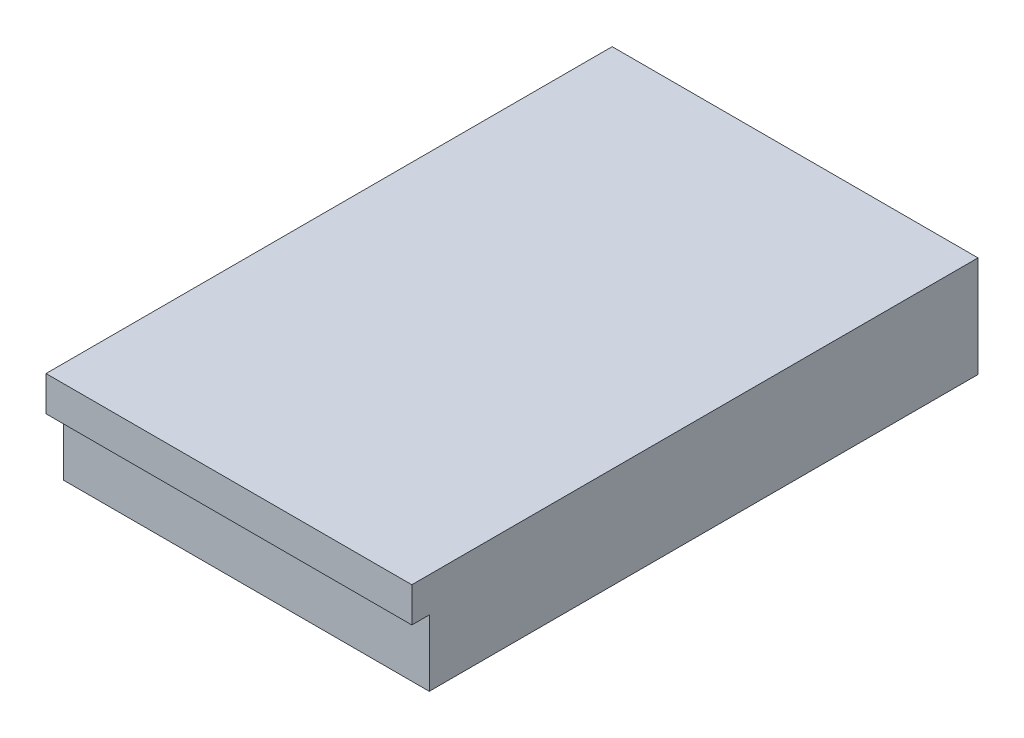
SolidWorks part; units mm, degrees
ref_plane "Front Plane" through (0, 0, 0) normal (0, 0, 1) x (1, 0, 0)
ref_plane "Top Plane" through (0, 0, 0) normal (0, 1, 0) x (1, 0, 0)
ref_plane "Right Plane" through (0, 0, 0) normal (1, 0, 0) x (0, 0, -1)
sketch "Sketch1" plane through (0, 0, 0) normal (0, 1, 0) x (1, 0, 0)
  line L1 (26.67, 40.005) -> (-26.67, 40.005)
  line L2 (26.67, 40.005) -> (26.67, -40.005)
  line L3 (26.67, -40.005) -> (-26.67, -40.005)
  line L4 (-26.67, 40.005) -> (-26.67, -40.005)
  line L5 (26.67, 40.005) -> (-26.67, -40.005) construction
  line L6 (26.67, -40.005) -> (-26.67, 40.005) construction
  point P0 (0, 0)
  dimension "D1" = 80.01
  dimension "D2" = 53.34
extrude "Boss-Extrude1" add sketch "Sketch1" along normal blind 14.732
sketch "Sketch2" plane through (0, 0, 40.005) normal (0, 0, 1) x (1, 0, 0)
  line L0 (26.67, 14.732) -> (26.67, 0) construction
  line L1 (-26.67, 14.732) -> (26.67, 14.732)
  line L2 (-26.67, 14.732) -> (-26.67, 9.652)
  line L3 (-26.67, 9.652) -> (26.67, 9.652)
  line L4 (26.67, 14.732) -> (26.67, 9.652)
  dimension "D1" = 5.08
extrude "Boss-Extrude2" add sketch "Sketch2" along normal blind 2.54
sketch "Sketch3" plane through (0, 14.732, 0) normal (0, 1, 0) x (-1, 0, 0)
  line L0 (26.67, -19.2566) -> (26.67, 42.545) construction
  line L1 (26.67, -40.005) -> (26.67, 42.545) construction
  text T0 "NDI"
